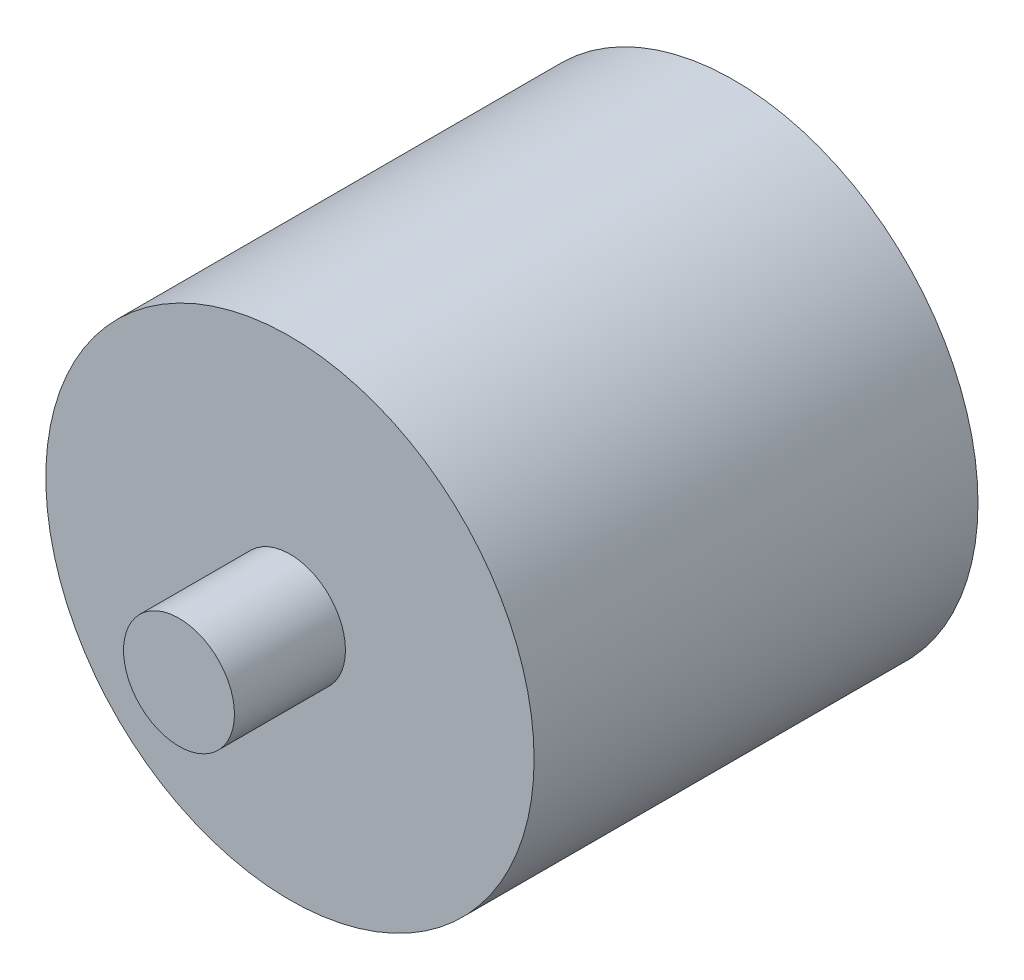
SolidWorks part; units mm, degrees
ref_plane "Front Plane" through (0, 0, 0) normal (0, 0, 1) x (1, 0, 0)
ref_plane "Top Plane" through (0, 0, 0) normal (0, 1, 0) x (1, 0, 0)
ref_plane "Right Plane" through (0, 0, 0) normal (1, 0, 0) x (0, 0, -1)
sketch "Sketch1" plane through (0, 0, 0) normal (0, 0, 1) x (1, 0, 0)
  circle A0 centre (0, 0) radius 11
  dimension "D1" = 22
extrude "Boss-Extrude1" add sketch "Sketch1" along normal blind 20
sketch "Sketch2" plane through (0, 0, 20) normal (0, 0, 1) x (1, 0, 0)
  circle A0 centre (0, 0) radius 2.5
  dimension "D1" = 5
extrude "Boss-Extrude2" add sketch "Sketch2" along normal blind 5
